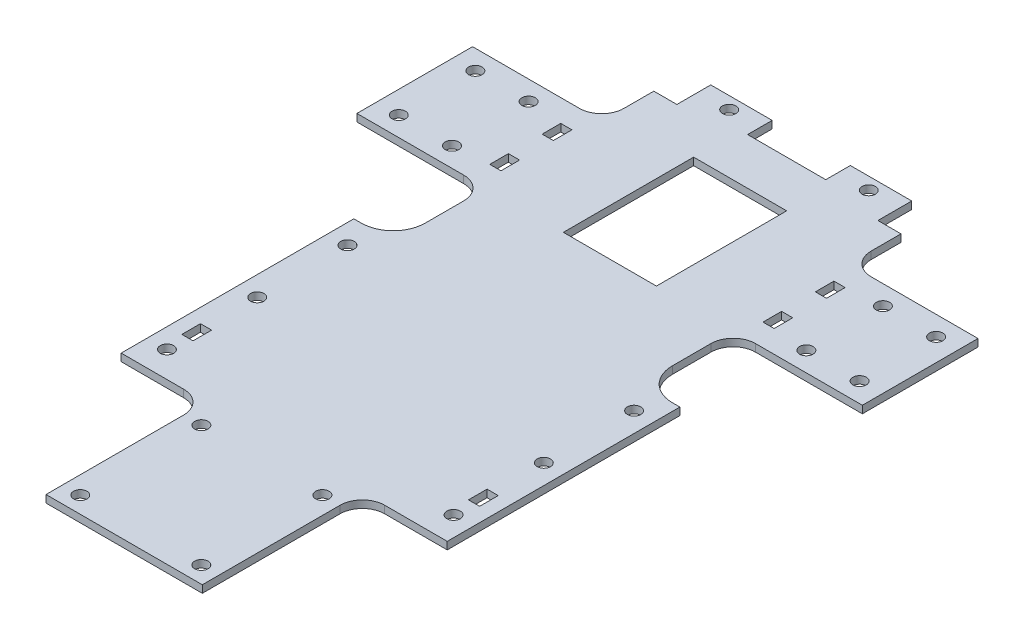
SolidWorks part; units mm, degrees
ref_plane "前视基准面" through (0, 0, 0) normal (0, 0, 1) x (1, 0, 0)
ref_plane "上视基准面" through (0, 0, 0) normal (0, 1, 0) x (1, 0, 0)
ref_plane "右视基准面" through (0, 0, 0) normal (1, 0, 0) x (0, 0, -1)
sketch "Sketch1" plane through (0, 0, 0) normal (0, 1, 0) x (1, 0, 0)
  line L1 (0, 0) -> (50, 0)
  line L2 (0, 0) -> (0, 9.1)
  line L3 (0, 9.1) -> (50, 9.1)
  line L4 (50, 0) -> (50, 9.1)
  dimension "D1" = 50
  dimension "D2" = 9.1
extrude "Boss-Extrude1" add sketch "Sketch1" along normal blind 2
sketch "Sketch2" plane through (0, 2, 0) normal (0, 1, 0) x (1, 0, 0)
  line L0 (50, 9.1) -> (0, 9.1) construction
  line L1 (12.5, 9.1) -> (37.5, 9.1)
  line L2 (12.5, 9.1) -> (12.5, 2.5)
  line L3 (12.5, 2.5) -> (37.5, 2.5)
  line L4 (37.5, 9.1) -> (37.5, 2.5)
  line L5 (0, 9.1) -> (0, 0) construction
  line L6 (50, 0) -> (50, 9.1) construction
  point P8 (50, 4.55)
  dimension "D1" = 6.6
  dimension "D2" = 12.5
  dimension "D3" = 12.5
extrude "Cut-Extrude1" cut sketch "Sketch2" against normal blind 2
sketch "Sketch3" plane through (0, 2, 0) normal (0, 1, 0) x (1, 0, 0)
  line L0 (12.5, 9.1) -> (0, 9.1) construction
  line L1 (50, 9.1) -> (37.5, 9.1) construction
  line L3 (37.5, 2.5) -> (37.5, 9.1) construction
  line L5 (0, 9.1) -> (0, 0) construction
  circle A0 centre (6.25, 5.8) radius 1.8
  circle A1 centre (43.75, 5.8) radius 1.8
  dimension "D1" = 3.6
  dimension "D2" = 3.6
  dimension "D4" = 3.3
  dimension "D3" = 3.3
  dimension "D5" = 6.25
  dimension "D6" = 6.25
extrude "Cut-Extrude2" cut sketch "Sketch3" against normal blind 2
sketch "Sketch4" plane through (0, 2, 0) normal (0, 1, 0) x (1, 0, 0)
  line L0 (0, 0) -> (50, 0) construction
  line L1 (-8.2, 0) -> (58.2, 0)
  line L2 (-8.2, 0) -> (-8.2, -130)
  line L3 (-8.2, -130) -> (58.2, -130)
  line L4 (58.2, 0) -> (58.2, -130)
  line L5 (12.5, 2.5) -> (37.5, 2.5) construction
  point P6 (25, 2.5)
  dimension "D1" = 130
  dimension "D2" = 0
  dimension "D3" = 33.2
  dimension "D4" = 66.4
extrude "Boss-Extrude2" add sketch "Sketch4" against normal blind 2
sketch "Sketch5" plane through (0, 0, 130) normal (0, 0, 1) x (1, 0, 0)
  line L1 (-8.2, 2) -> (58.2, 2)
  line L2 (-8.2, 2) -> (-8.2, 0)
  line L3 (-8.2, 0) -> (58.2, 0)
  line L4 (58.2, 2) -> (58.2, 0)
extrude "Boss-Extrude3" add sketch "Sketch5" along normal blind 2.5
sketch "Sketch6" plane through (0, 2, 0) normal (0, 1, 0) x (1, 0, 0)
  line L1 (-8.2, -132.5) -> (-16.8, -132.5)
  line L2 (-8.2, -132.5) -> (-8.2, -70)
  line L3 (-8.2, -70) -> (-16.8, -70)
  line L4 (-16.8, -132.5) -> (-16.8, -70)
  line L5 (58.2, -132.5) -> (66.8, -132.5)
  line L6 (58.2, -132.5) -> (58.2, -70)
  line L7 (58.2, -70) -> (66.8, -70)
  line L8 (66.8, -132.5) -> (66.8, -70)
  dimension "D1" = 8.6
  dimension "D2" = 8.6
  dimension "D3" = 62.5
  dimension "D4" = 62.5
extrude "Boss-Extrude4" add sketch "Sketch6" against normal blind 2
sketch "Sketch7" plane through (0, 2, 0) normal (0, 1, 0) x (1, 0, 0)
  line L0 (-13.5, -64.2883) -> (-13.5, -157.5169) construction
  line L1 (63.5, -64.2883) -> (63.5, -152.5529) construction
  line L2 (-16.8, -70) -> (-16.8, -132.5) construction
  line L3 (66.8, -132.5) -> (66.8, -70) construction
  line L4 (-8.2, -70) -> (-16.8, -70) construction
  line L5 (66.8, -132.5) -> (-16.8, -132.5) construction
  line L6 (66.8, -70) -> (58.2, -70) construction
  line L7 (-15, -115) -> (-12, -115)
  line L8 (-15, -115) -> (-15, -120)
  line L9 (-15, -120) -> (-12, -120)
  line L10 (-12, -115) -> (-12, -120)
  line L11 (62, -115) -> (65, -115)
  line L12 (62, -115) -> (62, -120)
  line L13 (62, -120) -> (65, -120)
  line L14 (65, -115) -> (65, -120)
  circle A0 centre (-13.5, -77) radius 1.8
  circle A1 centre (-13.5, -101.25) radius 1.8
  circle A2 centre (-13.5, -125.5) radius 1.8
  circle A3 centre (63.5, -77) radius 1.8
  circle A4 centre (63.5, -101.25) radius 1.8
  circle A5 centre (63.5, -125.5) radius 1.8
  dimension "D3" = 3.6
  dimension "D4" = 3.6
  dimension "D6" = 3.6
  dimension "D12" = 3.6
  dimension "D13" = 3.6
  dimension "D14" = 3.6
  dimension "D1" = 3.3
  dimension "D2" = 3.3
  dimension "D5" = 31.25
  dimension "D7" = 7
  dimension "D8" = 1.5
  dimension "D9" = 3
  dimension "D10" = 5
  dimension "D11" = 12.5
  dimension "D15" = 1.5
  dimension "D16" = 3
  dimension "D17" = 7
  dimension "D18" = 7
extrude "Cut-Extrude3" cut sketch "Sketch7" against normal blind 2
sketch "Sketch8" plane through (0, 2, 0) normal (0, 1, 0) x (1, 0, 0)
  line L0 (25, 2.5) -> (25, -143.8166) construction
  line L1 (12.5, 2.5) -> (37.5, 2.5) construction
  line L3 (12.5, 0) -> (37.5, 0)
  line L4 (12.5, 0) -> (12.5, -45)
  line L5 (12.5, -45) -> (37.5, -45)
  line L6 (37.5, 0) -> (37.5, -45)
  dimension "D1" = 25
  dimension "D2" = 12.5
  dimension "D3" = 45
extrude "Cut-Extrude4" cut sketch "Sketch8" against normal blind 20
sketch "Sketch9" plane through (0, 2, 0) normal (0, 1, 0) x (1, 0, 0)
  line L0 (37.5, -45) -> (37.5, 0) construction
  line L1 (12.5, 0) -> (37.5, 0)
  line L2 (12.5, 0) -> (12.5, -10)
  line L3 (12.5, -10) -> (37.5, -10)
  line L4 (37.5, 0) -> (37.5, -10)
  dimension "D1" = 10
extrude "Boss-Extrude5" add sketch "Sketch9" against normal blind 2
sketch "Sketch10" plane through (0, 2, 0) normal (0, 1, 0) x (1, 0, 0)
  line L0 (-8.2, 0) -> (-8.2, -70) construction
  line L1 (-8.2, -16) -> (-42.9, -16)
  line L2 (-8.2, -16) -> (-8.2, -43.07)
  line L3 (-8.2, -43.07) -> (-42.9, -43.07)
  line L4 (-42.9, -16) -> (-42.9, -43.07)
  line L5 (0, 0) -> (-8.2, 0) construction
  line L6 (58.2, -70) -> (58.2, 0) construction
  line L7 (58.2, -16) -> (92.9, -16)
  line L8 (58.2, -16) -> (58.2, -43.07)
  line L9 (58.2, -43.07) -> (92.9, -43.07)
  line L10 (92.9, -16) -> (92.9, -43.07)
  dimension "D1" = 16
  dimension "D2" = 27.07
  dimension "D3" = 34.7
  dimension "D4" = 34.7
extrude "Boss-Extrude6" add sketch "Sketch10" against normal blind 2
sketch "Sketch11" plane through (0, 2, 0) normal (0, 1, 0) x (1, 0, 0)
  line L0 (-48.2559, -39.82) -> (25.7485, -39.82) construction
  line L1 (-47.1851, -19.25) -> (20.7514, -19.25) construction
  line L2 (-8.2, -16) -> (-42.9, -16) construction
  line L3 (-42.9, -43.07) -> (-8.2, -43.07) construction
  line L4 (-42.9, -16) -> (-42.9, -43.07) construction
  circle A0 centre (-36.9, -19.25) radius 1.8
  circle A1 centre (-36.9, -39.82) radius 1.8
  circle A2 centre (-22.6, -19.25) radius 1.8
  circle A3 centre (-22.6, -39.82) radius 1.8
  dimension "D5" = 3.6
  dimension "D6" = 3.6
  dimension "D7" = 3.6
  dimension "D8" = 3.6
  dimension "D10" = 20.3
  dimension "D1" = 3.25
  dimension "D2" = 3.25
  dimension "D3" = 6
  dimension "D4" = 6
  dimension "D9" = 20.3
extrude "Cut-Extrude5" cut sketch "Sketch11" against normal blind 2
sketch "Sketch12" plane through (0, 2, 0) normal (0, 1, 0) x (1, 0, 0)
  line L0 (39.2942, -19.25) -> (115.8735, -19.25) construction
  line L1 (40.8036, -39.82) -> (109.9769, -39.82) construction
  line L2 (92.9, -43.07) -> (92.9, -16) construction
  circle A0 centre (72.6, -19.25) radius 1.8
  circle A1 centre (86.9, -19.25) radius 1.8
  circle A2 centre (72.6, -39.82) radius 1.8
  circle A3 centre (86.9, -39.82) radius 1.8
  dimension "D1" = 3.6
  dimension "D2" = 3.6
  dimension "D5" = 3.6
  dimension "D6" = 3.6
  dimension "D3" = 6
  dimension "D4" = 20.3
extrude "Cut-Extrude6" cut sketch "Sketch12" against normal blind 2
sketch "Sketch13" plane through (-42.9, 0, 0) normal (-1, 0, 0) x (0, 0, 1)
  line L1 (16, 2) -> (14, 2)
  line L2 (16, 2) -> (16, 0)
  line L3 (16, 0) -> (14, 0)
  line L4 (14, 2) -> (14, 0)
  line L5 (43.07, 2) -> (45.07, 2)
  line L6 (43.07, 2) -> (43.07, 0)
  line L7 (43.07, 0) -> (45.07, 0)
  line L8 (45.07, 2) -> (45.07, 0)
  dimension "D1" = 2
  dimension "D2" = 2
extrude "Boss-Extrude7" add sketch "Sketch13" against normal blind 44
sketch "Sketch14" plane through (92.9, 0, 0) normal (1, 0, 0) x (0, 0, -1)
  line L1 (-16, 2) -> (-14, 2)
  line L2 (-16, 2) -> (-16, 0)
  line L3 (-16, 0) -> (-14, 0)
  line L4 (-14, 2) -> (-14, 0)
  line L5 (-43.07, 0) -> (-45.07, 0)
  line L6 (-43.07, 0) -> (-43.07, 2)
  line L7 (-43.07, 2) -> (-45.07, 2)
  line L8 (-45.07, 0) -> (-45.07, 2)
  dimension "D1" = 2
  dimension "D2" = 2
extrude "Boss-Extrude8" add sketch "Sketch14" against normal blind 46
sketch "Sketch15" plane through (0, 2, 0) normal (0, 1, 0) x (1, 0, 0)
  line L0 (-19.562, -8) -> (-2.2953, -8) construction
  line L1 (-14.2, -3.5663) -> (-14.2, -21.6277) construction
  line L2 (-8.2, -14) -> (-42.9, -14) construction
  line L3 (-8.2, 0) -> (-8.2, -14) construction
  line L4 (-14.2, -14) -> (-8.2, -14)
  line L5 (-8.2, -14) -> (-8.2, -8)
  line L6 (58.2, -8) -> (58.2, -14)
  line L7 (58.2, -14) -> (58.2, 0) construction
  line L8 (58.2, -14) -> (64.2, -14)
  line L9 (58.2, -14) -> (92.9, -14) construction
  line L10 (-14.2, -45.07) -> (-8.2, -45.07)
  line L11 (-8.2, -45.07) -> (-42.9, -45.07) construction
  line L12 (-8.2, -45.07) -> (-8.2, -51.07)
  line L13 (-8.2, -45.07) -> (-8.2, -70) construction
  line L14 (64.2, -45.07) -> (58.2, -45.07)
  line L15 (58.2, -45.07) -> (92.9, -45.07) construction
  line L16 (58.2, -45.07) -> (58.2, -51.07)
  line L17 (58.2, -70) -> (58.2, -45.07) construction
  arc A0 (-8.2, -8) -> (-14.2, -14) centre (-14.2, -8) cw
  arc A1 (58.2, -8) -> (64.2, -14) centre (64.2, -8) ccw
  arc A2 (-14.2, -45.07) -> (-8.2, -51.07) centre (-14.2, -51.07) cw
  arc A3 (64.2, -45.07) -> (58.2, -51.07) centre (64.2, -51.07) ccw
  dimension "D1" = 6
  dimension "D2" = 6
  dimension "D3" = 6
  dimension "D4" = 6
  dimension "D5" = 6
extrude "Boss-Extrude9" add sketch "Sketch15" against normal blind 2 contours L5 A0 L4 | L10 A2 L12 | A3 L14 L16 | A1 L6 L8
sketch "Sketch16" plane through (0, 2, 0) normal (0, 1, 0) x (1, 0, 0)
  line L0 (66.8, -132.5) -> (-16.8, -132.5) construction
  line L1 (4, -132.5) -> (46, -132.5)
  line L2 (4, -132.5) -> (4, -175.5)
  line L3 (4, -175.5) -> (46, -175.5)
  line L4 (46, -132.5) -> (46, -175.5)
  line L5 (37.5, -45) -> (12.5, -45) construction
  point P6 (25, -45)
  dimension "D1" = 42
  dimension "D2" = 43
  dimension "D3" = 21
extrude "Boss-Extrude10" add sketch "Sketch16" against normal blind 2
sketch "Sketch18" plane through (0, 2, 0) normal (0, 1, 0) x (1, 0, 0)
  line L0 (4, -175.5) -> (46, -175.5) construction
  line L1 (4, -132.5) -> (4, -175.5) construction
  line L2 (46, -175.5) -> (46, -132.5) construction
  line L3 (4, -132.5) -> (-16.8, -132.5) construction
  line L4 (66.8, -132.5) -> (46, -132.5) construction
  circle A0 centre (8.74, -171.03) radius 1.8
  circle A1 centre (41.26, -171.03) radius 1.8
  circle A2 centre (8.74, -138.5) radius 1.8
  circle A3 centre (41.26, -138.5) radius 1.8
  dimension "D3" = 3.6
  dimension "D6" = 3.6
  dimension "D7" = 3.6
  dimension "D8" = 3.6
  dimension "D1" = 4.47
  dimension "D2" = 4.74
  dimension "D4" = 4.47
  dimension "D5" = 4.74
  dimension "D9" = 6
  dimension "D10" = 6
extrude "Cut-Extrude7" cut sketch "Sketch18" against normal blind 2
sketch "Sketch19" plane through (0, 2, 0) normal (0, 1, 0) x (1, 0, 0)
  line L0 (-16.8, -70) -> (-8.2, -70)
  line L1 (-8.2, -70) -> (-8.2, -61.4)
  line L2 (-8.2, -51.07) -> (-8.2, -70) construction
  line L3 (58.2, -61.4) -> (58.2, -70)
  line L4 (58.2, -70) -> (58.2, -51.07) construction
  line L5 (58.2, -70) -> (66.8, -70)
  line L6 (66.8, -132.5) -> (66.8, -70) construction
  arc A0 (-16.8, -70) -> (-8.2, -61.4) centre (-16.8, -61.4) ccw
  arc A1 (58.2, -61.4) -> (66.8, -70) centre (66.8, -61.4) ccw
  dimension "D1" = 8.6
extrude "Boss-Extrude11" add sketch "Sketch19" against normal blind 2 contours A0 L0 L1 | A1 L3 L5
sketch "Sketch20" plane through (0, 2, 0) normal (0, 1, 0) x (1, 0, 0)
  line L0 (-2, -132.5) -> (4, -132.5)
  line L1 (4, -132.5) -> (-16.8, -132.5) construction
  line L2 (4, -132.5) -> (4, -138.5)
  line L3 (4, -132.5) -> (4, -175.5) construction
  line L4 (46, -138.5) -> (46, -132.5)
  line L5 (46, -175.5) -> (46, -132.5) construction
  line L6 (46, -132.5) -> (52, -132.5)
  line L7 (66.8, -132.5) -> (46, -132.5) construction
  arc A0 (-2, -132.5) -> (4, -138.5) centre (-2, -138.5) cw
  arc A1 (52, -132.5) -> (46, -138.5) centre (52, -138.5) ccw
  dimension "D1" = 6
  dimension "D2" = 6
  dimension "D3" = 6
extrude "Boss-Extrude12" add sketch "Sketch20" against normal blind 2 contours L0 A0 L2 | A1 L6 L4
sketch "Sketch21" plane through (0, 0, -9.1) normal (0, 0, -1) x (-1, 0, 0)
  line L1 (-50, 2) -> (-52, 2)
  line L2 (-50, 2) -> (-50, 0)
  line L3 (-50, 0) -> (-52, 0)
  line L4 (-52, 2) -> (-52, 0)
  line L5 (-37.5, 2) -> (-35.5, 2)
  line L6 (-37.5, 2) -> (-37.5, 0)
  line L7 (-37.5, 0) -> (-35.5, 0)
  line L8 (-35.5, 2) -> (-35.5, 0)
  line L9 (-12.5, 2) -> (-14.5, 2)
  line L10 (-12.5, 2) -> (-12.5, 0)
  line L11 (-12.5, 0) -> (-14.5, 0)
  line L12 (-14.5, 2) -> (-14.5, 0)
  line L13 (0, 2) -> (2, 2)
  line L14 (0, 2) -> (0, 0)
  line L15 (0, 0) -> (2, 0)
  line L16 (2, 2) -> (2, 0)
  dimension "D1" = 2
  dimension "D2" = 2
  dimension "D3" = 2
  dimension "D4" = 2
extrude "Boss-Extrude13" add sketch "Sketch21" against normal blind 10
sketch "Sketch22" plane through (-16.8, 0, 0) normal (-1, 0, 0) x (0, 0, 1)
  line L1 (70, 2) -> (132.5, 2)
  line L2 (70, 2) -> (70, 0)
  line L3 (70, 0) -> (132.5, 0)
  line L4 (132.5, 2) -> (132.5, 0)
extrude "Boss-Extrude14" add sketch "Sketch22" along normal blind 2
sketch "Sketch23" plane through (66.8, 0, 0) normal (1, 0, 0) x (0, 0, -1)
  line L1 (-70, 0) -> (-132.5, 0)
  line L2 (-70, 0) -> (-70, 2)
  line L3 (-70, 2) -> (-132.5, 2)
  line L4 (-132.5, 0) -> (-132.5, 2)
extrude "Boss-Extrude15" add sketch "Sketch23" along normal blind 2
sketch "Sketch25" plane through (0, 2, 0) normal (0, 1, 0) x (1, 0, 0)
  line L0 (-11.7, -6.4239) -> (-11.7, -56.5762) construction
  line L1 (-8.2, 0) -> (-8.2, -8) construction
  line L2 (61.7, -6.4239) -> (61.7, -56.5762) construction
  line L3 (58.2, -8) -> (58.2, 0) construction
  line L4 (-14.2, -14) -> (-42.9, -14) construction
  line L5 (-13.2, -20) -> (-10.2, -20)
  line L6 (-13.2, -20) -> (-13.2, -25)
  line L7 (-13.2, -25) -> (-10.2, -25)
  line L8 (-10.2, -20) -> (-10.2, -25)
  line L9 (-14.2, -45.07) -> (-42.9, -45.07) construction
  line L10 (-13.2, -34.07) -> (-10.2, -34.07)
  line L11 (-13.2, -34.07) -> (-13.2, -39.07)
  line L12 (-13.2, -39.07) -> (-10.2, -39.07)
  line L13 (-10.2, -34.07) -> (-10.2, -39.07)
  line L14 (64.2, -14) -> (92.9, -14) construction
  line L15 (60.2, -20) -> (63.2, -20)
  line L16 (60.2, -20) -> (60.2, -25)
  line L17 (60.2, -25) -> (63.2, -25)
  line L18 (63.2, -20) -> (63.2, -25)
  line L19 (60.2, -34.07) -> (63.2, -34.07)
  line L20 (60.2, -34.07) -> (60.2, -39.07)
  line L21 (60.2, -39.07) -> (63.2, -39.07)
  line L22 (63.2, -34.07) -> (63.2, -39.07)
  line L23 (64.2, -45.07) -> (92.9, -45.07) construction
  dimension "D1" = 3.5
  dimension "D2" = 3.5
  dimension "D3" = 3
  dimension "D4" = 1.5
  dimension "D5" = 5
  dimension "D6" = 6
  dimension "D7" = 5
  dimension "D8" = 6
  dimension "D9" = 3
  dimension "D10" = 1.5
  dimension "D11" = 1.5
  dimension "D12" = 3
  dimension "D13" = 1.5
  dimension "D14" = 3
  dimension "D15" = 6
  dimension "D16" = 6
extrude "Cut-Extrude8" cut sketch "Sketch25" against normal blind 10
